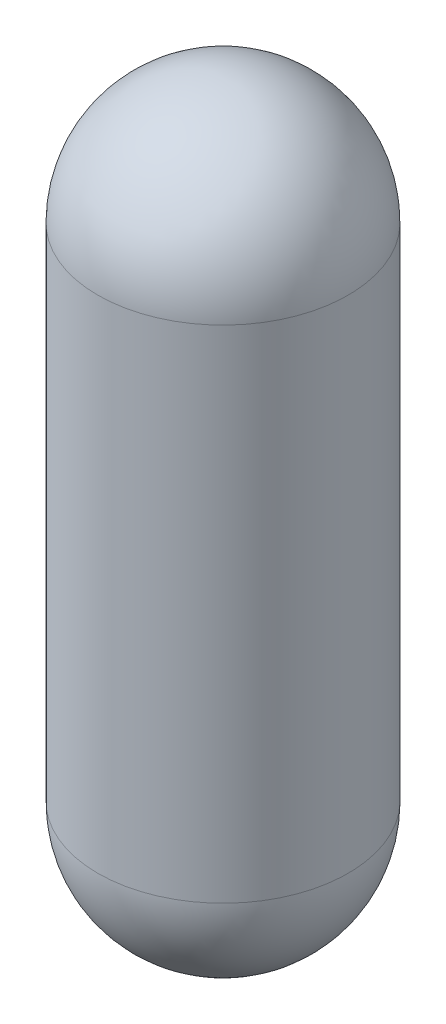
SolidWorks part; units mm, degrees
ref_plane "Front Plane" through (0, 0, 0) normal (0, 0, 1) x (1, 0, 0)
ref_plane "Top Plane" through (0, 0, 0) normal (0, 1, 0) x (1, 0, 0)
ref_plane "Right Plane" through (0, 0, 0) normal (1, 0, 0) x (0, 0, -1)
sketch "Sketch1" plane through (0, 0, 0) normal (0, 1, 0) x (1, 0, 0)
  circle A0 centre (0, 0) radius 50.8
  dimension "D1" = 101.6
extrude "Boss-Extrude1" add sketch "Sketch1" against normal mid plane 203.2
sketch "Sketch3" plane through (0, 0, 0) normal (1, 0, 0) x (0, 0, -1)
  line L0 (0, 101.6) -> (-50.8, 101.6)
  line L2 (50.8, 101.6) -> (-50.8, 101.6) construction
  line L3 (0, 152.4) -> (0, 101.6)
  arc A0 (-50.8, 101.6) -> (0, 152.4) centre (0, 101.6) cw
  point P8 (0, 0)
revolve "Revolve1" add sketch "Sketch3" angle 360 about L3
mirror "Mirror1" about plane through (0, 0, 0) normal (0, 1, 0) of "Revolve1"
